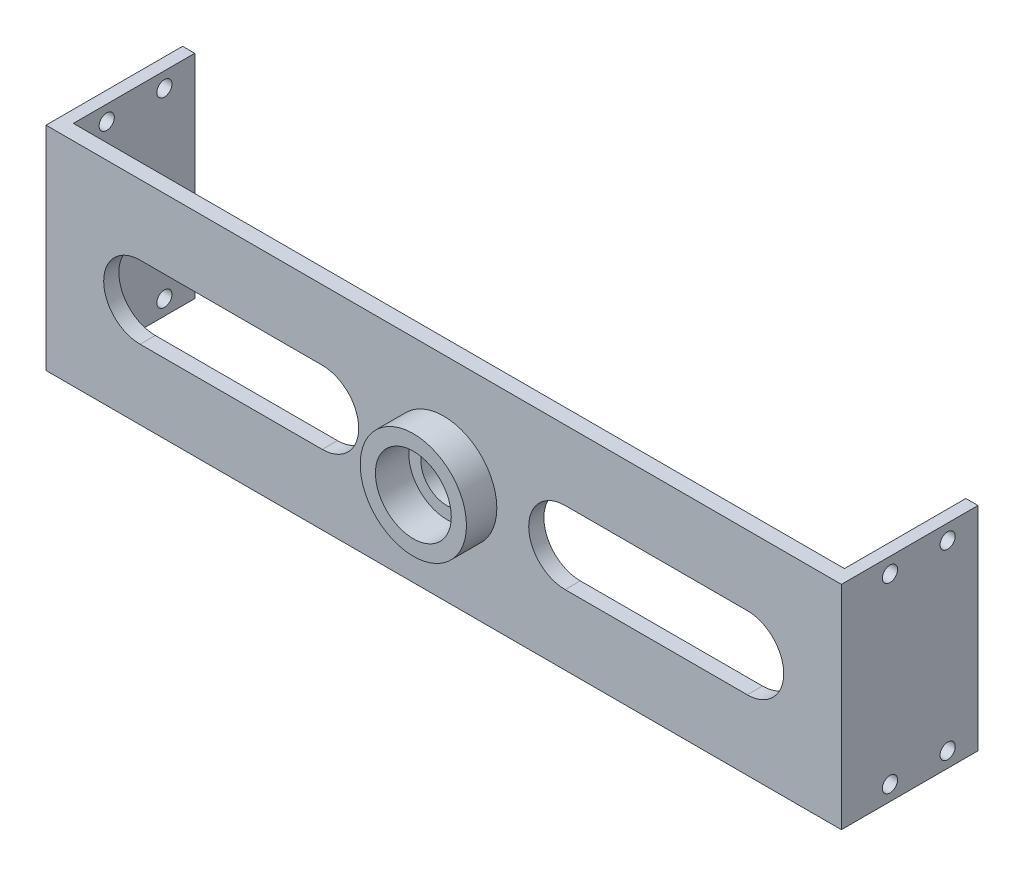
SolidWorks part; units mm, degrees
ref_plane "Plan de face" through (0, 0, 0) normal (0, 0, 1) x (1, 0, 0)
ref_plane "Plan de dessus" through (0, 0, 0) normal (0, 1, 0) x (1, 0, 0)
ref_plane "Plan de droite" through (0, 0, 0) normal (1, 0, 0) x (0, 0, -1)
sketch "Esquisse1" plane through (0, 0, 0) normal (0, 0, 1) x (1, 0, 0)
  line L1 (-127, 35) -> (127, 35)
  line L2 (-127, 35) -> (-127, -35)
  line L3 (-127, -35) -> (127, -35)
  line L4 (127, 35) -> (127, -35)
  line L5 (-127, 35) -> (127, -35) construction
  line L6 (-127, -35) -> (127, 35) construction
  point P0 (0, 0)
  dimension "D1" = 254
  dimension "D2" = 70
extrude "Boss.-Extru.1" add sketch "Esquisse1" along normal blind 5
sketch "Esquisse2" plane through (0, 0, 5) normal (0, 0, 1) x (1, 0, 0)
  circle A0 centre (0, 0) radius 12.5
  dimension "D1" = 25
extrude "Enlèv. mat.-Extru.1" cut sketch "Esquisse2" against normal through all
sketch "Esquisse3" plane through (0, 0, 5) normal (0, 0, 1) x (1, 0, 0)
  circle A0 centre (0, 0) radius 12.5 construction
  circle A1 centre (0, 0) radius 12.5
  circle A2 centre (0, 0) radius 17.5
  dimension "D1" = 5
extrude "Boss.-Extru.2" add sketch "Esquisse3" along normal blind 10
sketch "Esquisse4" plane through (0, 0, 5) normal (0, 0, 1) x (1, 0, 0)
  line L0 (-100, 0) -> (-40, 0) construction
  line L1 (-100, 12) -> (-40, 12)
  line L2 (-100, -12) -> (-40, -12)
  line L3 (0, 41.1136) -> (0, 0) construction
  line L4 (100, 0) -> (40, 0) construction
  line L5 (100, 12) -> (40, 12)
  line L6 (100, -12) -> (40, -12)
  arc A0 (-100, 12) -> (-100, -12) centre (-100, 0) ccw
  arc A1 (-40, -12) -> (-40, 12) centre (-40, 0) ccw
  arc A2 (100, 12) -> (100, -12) centre (100, 0) cw
  arc A3 (40, -12) -> (40, 12) centre (40, 0) cw
  point P3 (-70, 0)
  point P12 (70, 0)
  dimension "D3" = 12
  dimension "D1" = 60
  dimension "D2" = 40
extrude "Enlèv. mat.-Extru.2" cut sketch "Esquisse4" against normal through all
sketch "Esquisse5" plane through (-127, 0, 0) normal (-1, 0, 0) x (0, 0, 1)
  line L5 (5, 35) -> (-40, 35)
  line L6 (5, 35) -> (5, -35)
  line L7 (5, -35) -> (-40, -35)
  line L8 (-40, 35) -> (-40, -35)
  line L9 (5, 35) -> (-40, -35) construction
  line L10 (5, -35) -> (-40, 35) construction
  point P4 (-17.5, 0)
  dimension "D1" = 70
  dimension "D2" = 45
extrude "Boss.-Extru.3" add sketch "Esquisse5" along normal blind 4
sketch "Esquisse6" plane through (127, 0, 0) normal (1, 0, 0) x (0, 0, -1)
  line L12 (-5, 35) -> (-5, -35)
  line L13 (40, 35) -> (-5, 35)
  line L14 (40, -35) -> (40, 35)
  line L15 (-5, -35) -> (40, -35)
  line L16 (-5, 35) -> (-5, -35)
  line L17 (40, 35) -> (-5, 35)
  line L18 (40, -35) -> (40, 35)
  line L19 (-5, -35) -> (40, -35)
  point P2 (0, 0)
  point P4 (0, 0)
  dimension "D1" = 0
extrude "Boss.-Extru.4" add sketch "Esquisse6" along normal blind 4
sketch "Esquisse7" plane through (-131, 0, 0) normal (-1, 0, 0) x (0, 0, 1)
  circle A0 centre (-11, 30) radius 2.5
  circle A1 centre (-11, -30) radius 2.5
  circle A2 centre (-30, 30) radius 2.5
  circle A3 centre (-30, -30) radius 2.5
  point P9 (0, 0)
  point P10 (0, 0)
  point P11 (0, 0)
  dimension "D3" = 5
  dimension "D1" = 60
  dimension "D2" = 30
  dimension "D5" = 11
  dimension "D6" = 19
extrude "Enlèv. mat.-Extru.3" cut sketch "Esquisse7" against normal through all
sketch "Esquisse8" plane through (0, 0, 0) normal (0, 0, -1) x (-1, 0, 0)
  circle A0 centre (0, 0) radius 12.5 construction
  circle A1 centre (0, 0) radius 12.5
  circle A3 centre (0, 0) radius 8.5
  dimension "D1" = 4
extrude "Boss.-Extru.5" add sketch "Esquisse8" against normal blind 4
